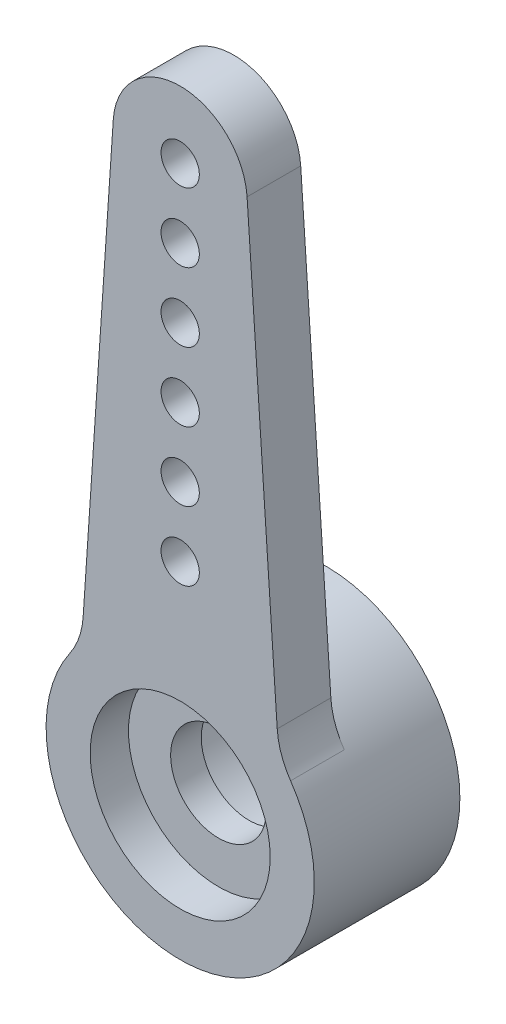
SolidWorks part; units mm, degrees
ref_plane "Ebene vorne" through (0, 0, 0) normal (0, 0, 1) x (1, 0, 0)
ref_plane "Ebene oben" through (0, 0, 0) normal (0, 1, 0) x (1, 0, 0)
ref_plane "Ebene rechts" through (0, 0, 0) normal (1, 0, 0) x (0, 0, -1)
sketch "Skizze1" plane through (0, 0, 0) normal (0, 0, 1) x (1, 0, 0)
  circle A0 centre (0, 0) radius 3.5
  circle A1 centre (0, 0) radius 1.25
  dimension "D1" = 7
  dimension "D2" = 2.5
extrude "Aufsatz-Linear austragen1" add sketch "Skizze1" along normal blind 3.8
sketch "Skizze2" plane through (0, 0, 3.8) normal (0, 0, 1) x (1, 0, 0)
  line L0 (0, 0) -> (0, 14.5) construction
  line L1 (2.65, 1.25) -> (-2.65, 1.25)
  line L2 (-2.65, 1.25) -> (-1.746, 14.6181)
  line L3 (2.65, 1.25) -> (1.746, 14.6181)
  line L4 (0, -1.8) -> (0, 12.7) construction
  line L5 (0, -3.6) -> (0, 10.9) construction
  line L6 (0, -5.4) -> (0, 9.1) construction
  line L7 (0, -7.2) -> (0, 7.3) construction
  circle A0 centre (0, 14.5) radius 0.5
  arc A1 (1.746, 14.6181) -> (-1.746, 14.6181) centre (0, 14.5) ccw
  circle A2 centre (0, 0) radius 1.25 construction
  circle A3 centre (0, 12.7) radius 0.5
  circle A4 centre (0, 10.9) radius 0.5
  circle A5 centre (0, 9.1) radius 0.5
  circle A6 centre (0, 7.3) radius 0.5
  circle A7 centre (0, 5.5) radius 0.5
  point P9 (0, 1.25)
  dimension "D2" = 1
  dimension "D4" = 3.5
  dimension "D5" = 1.8
  dimension "D1" = 14.5
  dimension "D3" = 5.3
  dimension "D6" = 5
extrude "Aufsatz-Linear austragen2" add sketch "Skizze2" against normal blind 1.4
sketch "Skizze3" plane through (0, 0, 3.8) normal (0, 0, 1) x (1, 0, 0)
  circle A0 centre (0, 0) radius 2.35
  dimension "D1" = 4.7
extrude "Schnitt-Linear austragen1" cut sketch "Skizze3" against normal blind 1
sketch "Skizze4" plane through (0, 0, 0) normal (0, 0, -1) x (-1, 0, 0)
  circle A0 centre (0, 0) radius 2.35
  dimension "D1" = 4.7
extrude "Schnitt-Linear austragen2" cut sketch "Skizze4" against normal blind 2
fillet "Verrundung1" radius 2 2 edges at (-2.5742, 2.3714, 3.1) (2.5742, 2.3714, 3.1)
